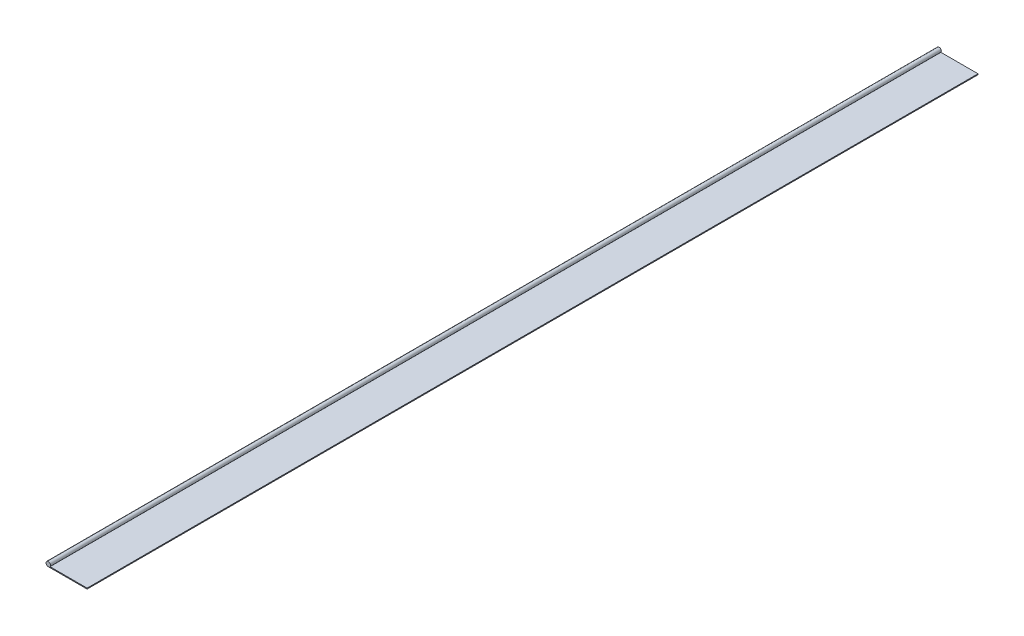
SolidWorks part; units mm, degrees
ref_plane "Front Plane" through (0, 0, 0) normal (0, 0, 1) x (1, 0, 0)
ref_plane "Top Plane" through (0, 0, 0) normal (0, 1, 0) x (1, 0, 0)
ref_plane "Right Plane" through (0, 0, 0) normal (1, 0, 0) x (0, 0, -1)
sketch "Sketch1" plane through (0, 0, 0) normal (0, 0, 1) x (1, 0, 0)
  line L0 (0, -1.5) -> (26.2, -1.5)
  line L4 (26.9325, 0.45) -> (26.9325, -0.45)
  line L5 (26.2, -1.5) -> (26.2, -0.9)
  line L6 (26.2, -0.9) -> (1.2, -0.9)
  arc A0 (1.2, -0.9) -> (0, -1.5) centre (0, 0) ccw
  point P1 (26.9325, 0)
  dimension "D1" = 3
  dimension "D2" = 25
  dimension "D3" = 0.9
  dimension "D4" = 0.6
extrude "Boss-Extrude1" add sketch "Sketch1" along normal blind 600 contours L6 A0 L0 L5
